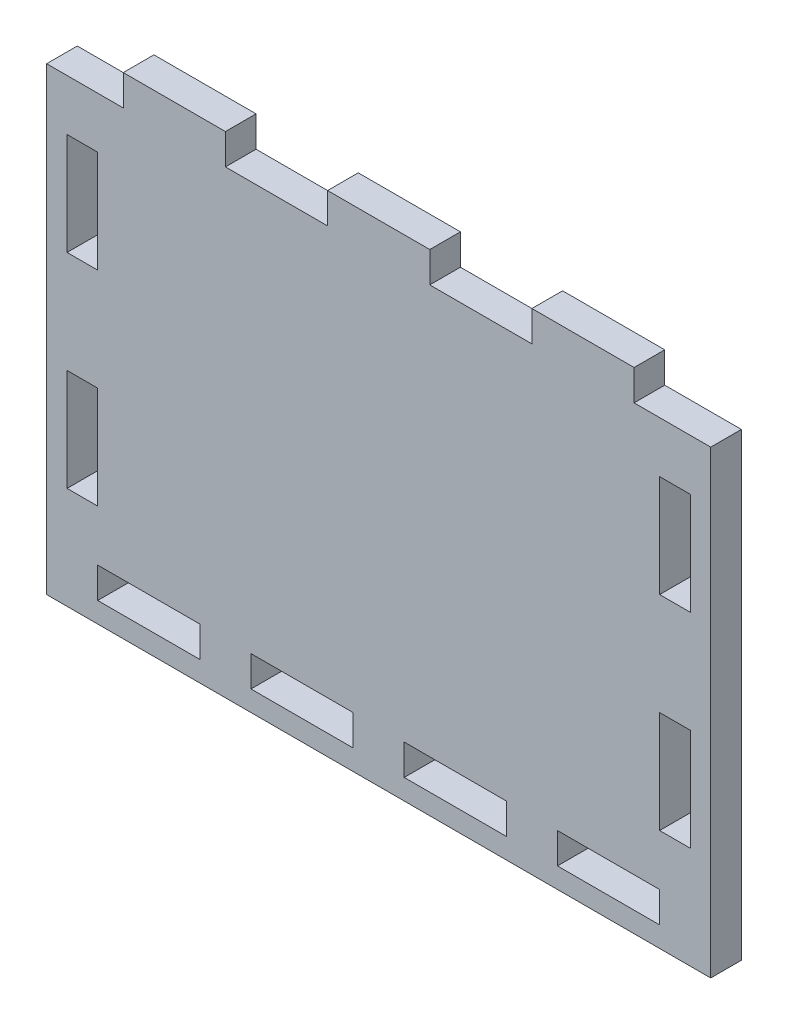
SolidWorks part; units mm, degrees
ref_plane "前视基准面" through (0, 0, 0) normal (0, 0, 1) x (1, 0, 0)
ref_plane "上视基准面" through (0, 0, 0) normal (0, 1, 0) x (1, 0, 0)
ref_plane "右视基准面" through (0, 0, 0) normal (1, 0, 0) x (0, 0, -1)
sketch "草图1" plane through (0, 0, 0) normal (0, 0, 1) x (1, 0, 0)
  line L0 (-4.9018, 22.086) -> (-4.9018, 25.086)
  line L1 (-32.4018, 22.086) -> (-24.9018, 22.086)
  line L2 (-32.4018, 22.086) -> (-32.4018, -22.914)
  line L3 (-32.4018, -22.914) -> (32.5982, -22.914)
  line L4 (32.5982, 22.086) -> (32.5982, -22.914)
  line L5 (-32.4018, 22.086) -> (32.5982, -22.914) construction
  line L6 (-32.4018, -22.914) -> (32.5982, 22.086) construction
  line L7 (-24.9018, 22.086) -> (-24.9018, 25.086)
  line L8 (-24.9018, 25.086) -> (-14.9018, 25.086)
  line L9 (-14.9018, 22.086) -> (-14.9018, 25.086)
  line L10 (5.0982, 22.086) -> (5.0982, 25.086)
  line L11 (-4.9018, 25.086) -> (5.0982, 25.086)
  line L12 (15.0982, 22.086) -> (15.0982, 25.086)
  line L13 (25.0982, 22.086) -> (25.0982, 25.086)
  line L14 (15.0982, 25.086) -> (25.0982, 25.086)
  line L15 (-12.4018, -20.914) -> (-12.4018, -17.914)
  line L16 (-27.4018, -20.914) -> (-17.4018, -20.914)
  line L17 (-27.4018, -20.914) -> (-27.4018, -17.914)
  line L18 (-27.4018, -17.914) -> (-17.4018, -17.914)
  line L19 (-17.4018, -20.914) -> (-17.4018, -17.914)
  line L20 (-12.4018, -20.914) -> (-2.4018, -20.914)
  line L21 (-2.4018, -20.914) -> (-2.4018, -17.914)
  line L22 (-12.4018, -17.914) -> (-2.4018, -17.914)
  line L23 (2.5982, -20.914) -> (2.5982, -17.914)
  line L24 (2.5982, -20.914) -> (12.5982, -20.914)
  line L25 (12.5982, -20.914) -> (12.5982, -17.914)
  line L26 (2.5982, -17.914) -> (12.5982, -17.914)
  line L27 (17.5982, -20.914) -> (17.5982, -17.914)
  line L28 (17.5982, -20.914) -> (27.5982, -20.914)
  line L29 (27.5982, -20.914) -> (27.5982, -17.914)
  line L30 (17.5982, -17.914) -> (27.5982, -17.914)
  line L31 (-30.4018, -2.914) -> (-27.4018, -2.914)
  line L32 (-27.4018, -12.914) -> (-27.4018, -2.914)
  line L33 (-30.4018, -12.914) -> (-27.4018, -12.914)
  line L34 (-30.4018, -12.914) -> (-30.4018, -2.914)
  line L35 (-14.9018, 22.086) -> (-4.9018, 22.086)
  line L36 (5.0982, 22.086) -> (15.0982, 22.086)
  line L37 (25.0982, 22.086) -> (32.5982, 22.086)
  line L38 (-30.4018, 17.086) -> (-27.4018, 17.086)
  line L39 (-27.4018, 7.086) -> (-27.4018, 17.086)
  line L40 (-30.4018, 7.086) -> (-27.4018, 7.086)
  line L41 (-30.4018, 7.086) -> (-30.4018, 17.086)
  line L42 (30.5982, -12.914) -> (30.5982, -2.914)
  line L43 (30.5982, -12.914) -> (27.5982, -12.914)
  line L44 (27.5982, -12.914) -> (27.5982, -2.914)
  line L45 (30.5982, -2.914) -> (27.5982, -2.914)
  line L46 (30.5982, 7.086) -> (30.5982, 17.086)
  line L47 (30.5982, 7.086) -> (27.5982, 7.086)
  line L48 (27.5982, 7.086) -> (27.5982, 17.086)
  line L49 (30.5982, 17.086) -> (27.5982, 17.086)
  point P0 (0.0982, -0.414)
  dimension "D1" = 65
  dimension "D2" = 45
  dimension "D3" = 10
  dimension "D4" = 3
  dimension "D5" = 7.5
  dimension "D6" = 10
  dimension "D7" = 3
  dimension "D8" = 2
  dimension "D9" = 5
  dimension "D10" = 10
  dimension "D11" = 10
  dimension "D12" = 3
extrude "凸台-拉伸1" add sketch "草图1" along normal blind 3
